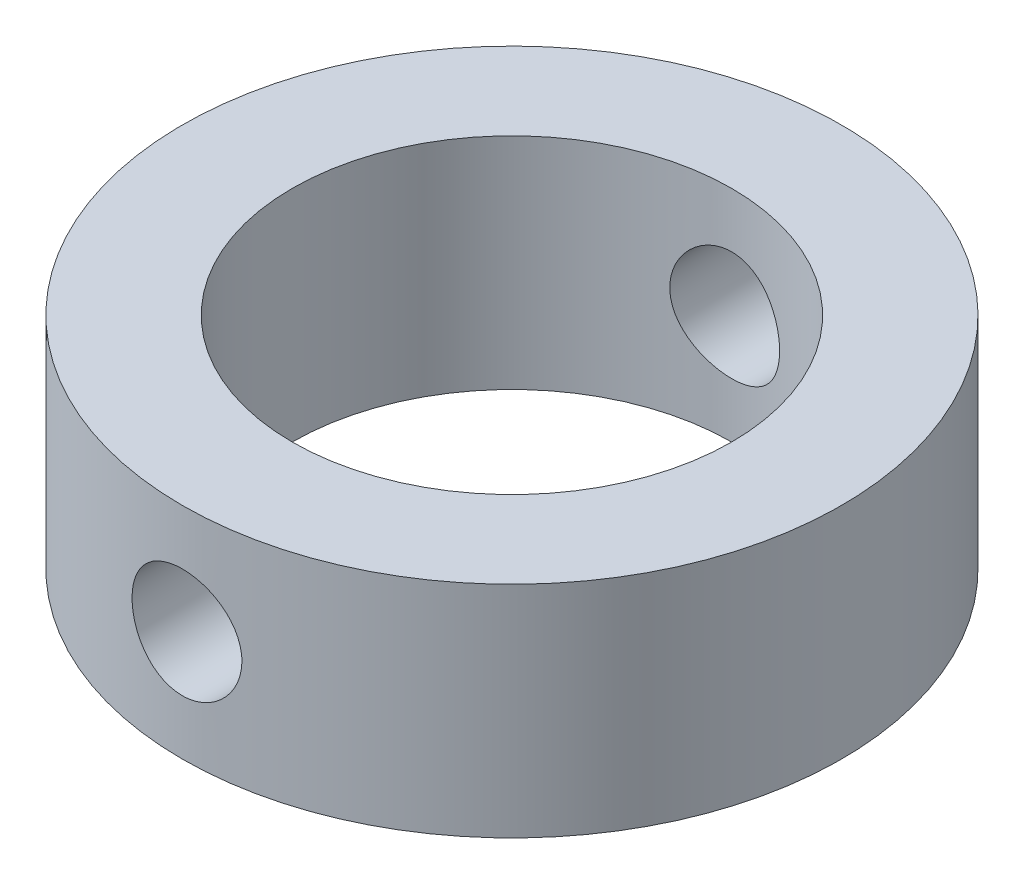
SolidWorks part; units mm, degrees
material "AISI 1020"
ref_plane "Front Plane" through (0, 0, 0) normal (0, 0, 1) x (1, 0, 0)
ref_plane "Top Plane" through (0, 0, 0) normal (0, 1, 0) x (1, 0, 0)
ref_plane "Right Plane" through (0, 0, 0) normal (1, 0, 0) x (0, 0, -1)
sketch "Sketch2" plane through (0, 0, 0) normal (0, 1, 0) x (1, 0, 0)
  circle A0 centre (0, 0) radius 15
  dimension "D1" = 30
extrude "Boss-Extrude1" add sketch "Sketch2" along normal blind 10
sketch "Sketch3" plane through (0, 10, 0) normal (0, 1, 0) x (1, 0, 0)
  circle A0 centre (0, 0) radius 10
  dimension "D1" = 20
extrude "Cut-Extrude1" cut sketch "Sketch3" against normal through all contours A0
sketch "Sketch4" plane through (0, 0, 0) normal (0, 0, 1) x (1, 0, 0)
  line L0 (15, 0) -> (15, 10) construction
  line L1 (-15, 0) -> (15, 0) construction
  circle A0 centre (0, 5) radius 2.5
  dimension "D1" = 5
  dimension "D2" = 15
  dimension "D3" = 5
extrude "Cut-Extrude2" cut sketch "Sketch4" against normal through all both and the other way through all contours A0
